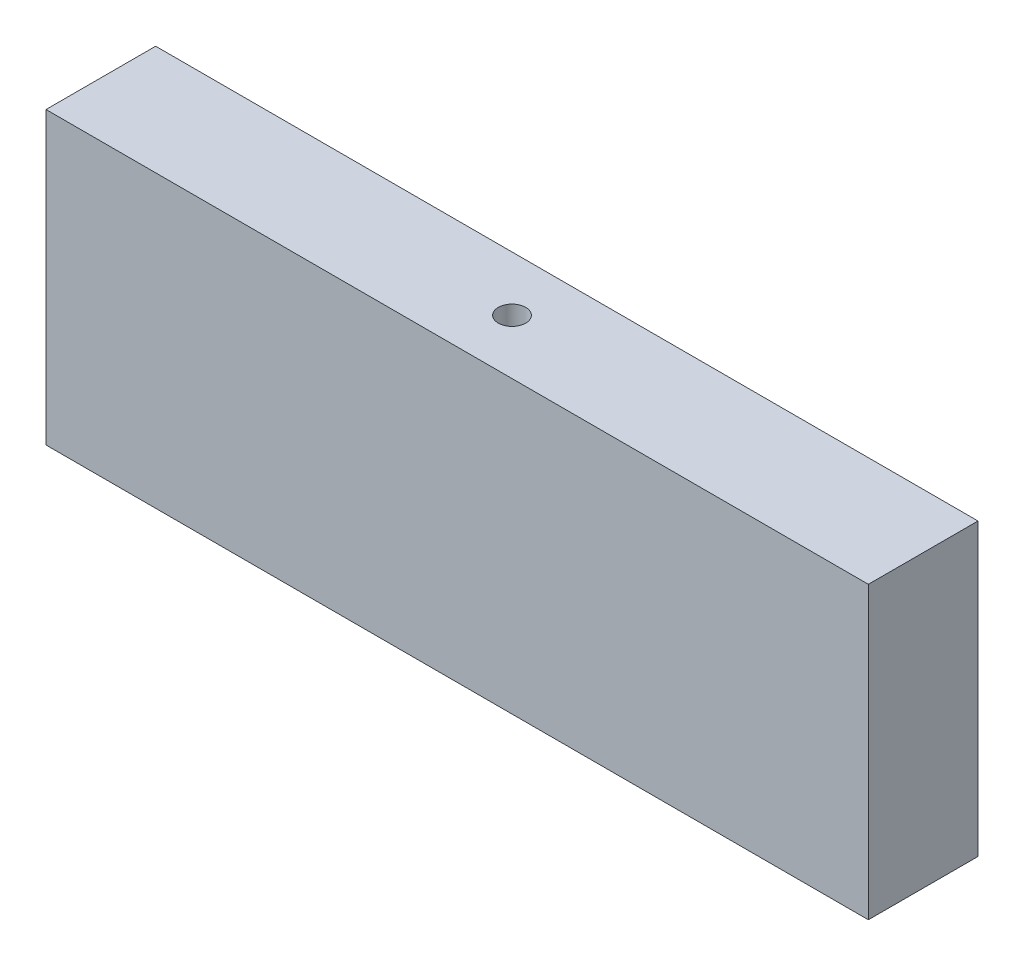
SolidWorks part; units mm, degrees
material "Кедр"
ref_plane "Спереди" through (0, 0, 0) normal (0, 0, 1) x (1, 0, 0)
ref_plane "Сверху" through (0, 0, 0) normal (0, 1, 0) x (1, 0, 0)
ref_plane "Справа" through (0, 0, 0) normal (1, 0, 0) x (0, 0, -1)
sketch "Эскиз1" plane through (0, 0, 0) normal (0, 0, 1) x (1, 0, 0)
  line L1 (-75, 26.5) -> (75, 26.5)
  line L2 (-75, 26.5) -> (-75, -26.5)
  line L3 (-75, -26.5) -> (75, -26.5)
  line L4 (75, 26.5) -> (75, -26.5)
  line L5 (-75, 26.5) -> (75, -26.5) construction
  line L6 (-75, -26.5) -> (75, 26.5) construction
  point P0 (0, 0)
  dimension "D1" = 150
  dimension "D2" = 53
extrude "Бобышка-Вытянуть1" add sketch "Эскиз1" along normal mid plane 20
sketch "Эскиз2" plane through (0, 0, 0) normal (0, 1, 0) x (1, 0, 0)
  circle A0 centre (0, 0) radius 2.5
  dimension "D1" = 5
extrude "Вырез-Вытянуть1" cut sketch "Эскиз2" against normal through all and the other way through all
equation "\"Толщина Стеклопакета\"= 51"
equation "\"Толщина Подушек\"= 2"
equation "\"Высота Деревянной Подкладки\"= \"Толщина Стеклопакета\" + \"Толщина Подушек\""
equation "\"Высота Швеллера\"= \"Высота Деревянной Подкладки\""
equation "\"D2@Эскиз1\"=\"Высота Деревянной Подкладки\""
